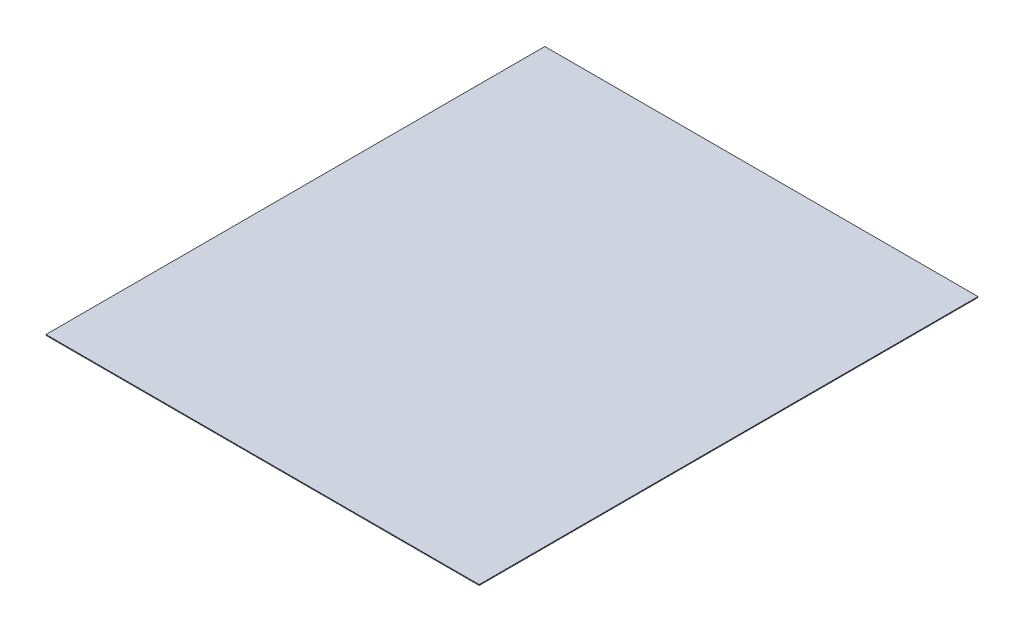
SolidWorks part; units mm, degrees
ref_plane "Front Plane" through (0, 0, 0) normal (0, 0, 1) x (1, 0, 0)
ref_plane "Top Plane" through (0, 0, 0) normal (0, 1, 0) x (1, 0, 0)
ref_plane "Right Plane" through (0, 0, 0) normal (1, 0, 0) x (0, 0, -1)
sketch "Sketch1" plane through (0, 0, 0) normal (0, 1, 0) x (1, 0, 0)
  line L0 (-875.7828, -917.2453) -> (800.6172, -917.2453)
  line L1 (-875.7828, -917.2453) -> (-875.7828, 1013.1547)
  line L2 (-875.7828, 1013.1547) -> (800.6172, 1013.1547)
  line L3 (800.6172, -917.2453) -> (800.6172, 1013.1547)
  dimension "D1" = 1930.4
  dimension "D2" = 1676.4
extrude "Boss-Extrude1" add sketch "Sketch1" along normal blind 3.175
